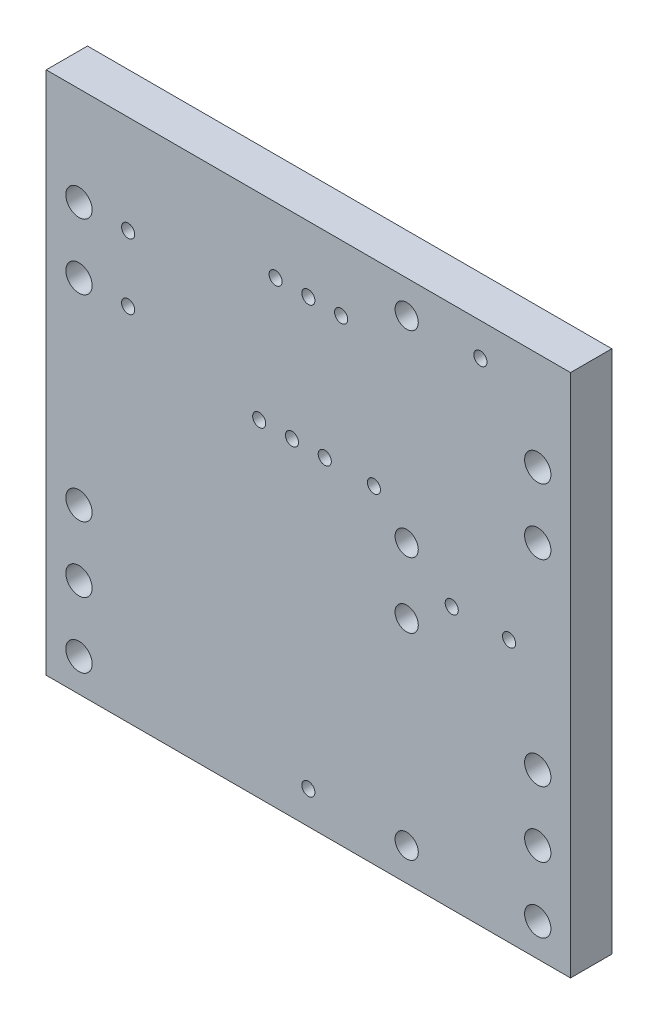
SolidWorks part; units mm, degrees
ref_plane "Front Plane" through (0, 0, 0) normal (0, 0, 1) x (1, 0, 0)
ref_plane "Top Plane" through (0, 0, 0) normal (0, 1, 0) x (1, 0, 0)
ref_plane "Right Plane" through (0, 0, 0) normal (1, 0, 0) x (0, 0, -1)
ref_plane "Dielectric_Layer Layer 1" through (0, 0, 1.6) normal (0, 0, 1) x (1, 0, 0)
sketch "Sketch1" plane through (0, 0, 0) normal (0, 0, 1) x (1, 0, 0)
  line L0 (0, 0) -> (20.32, 0)
  line L1 (20.32, 0) -> (20.32, 20.32)
  line L2 (20.32, 20.32) -> (0, 20.32)
  line L3 (0, 20.32) -> (0, 0)
extrude "Board_Outline" add sketch "Sketch1" along normal blind 1.6 separate body
sketch "Sketch2" plane through (0, 0, 0) normal (0, 0, 1) x (1, 0, 0)
  circle A0 centre (9.525, 12.7) radius 0.254
  circle A1 centre (11.43, 17.78) radius 0.254
  circle A2 centre (10.16, 17.78) radius 0.254
  circle A3 centre (10.795, 12.7) radius 0.254
  circle A4 centre (3.175, 13.97) radius 0.254
  circle A5 centre (8.89, 17.78) radius 0.254
  circle A6 centre (15.7163, 10.16) radius 0.254
  circle A7 centre (16.8275, 19.05) radius 0.254
  circle A8 centre (8.255, 12.7) radius 0.254
  circle A9 centre (17.9388, 10.16) radius 0.254
  circle A10 centre (12.7, 12.7) radius 0.254
  circle A11 centre (10.16, 1.27) radius 0.254
  circle A12 centre (3.175, 16.51) radius 0.254
extrude "NPTH" cut sketch "Sketch2" along normal through all
sketch "Sketch3" plane through (0, 0, 0) normal (0, 0, 1) x (1, 0, 0)
  circle A0 centre (1.27, 1.27) radius 0.51
  circle A1 centre (1.27, 3.81) radius 0.51
  circle A2 centre (1.27, 6.35) radius 0.51
  circle A3 centre (19.05, 16.51) radius 0.51
  circle A4 centre (19.05, 13.97) radius 0.51
  circle A5 centre (1.27, 16.51) radius 0.51
  circle A6 centre (1.27, 13.97) radius 0.51
  circle A7 centre (19.05, 1.27) radius 0.51
  circle A8 centre (19.05, 3.81) radius 0.51
  circle A9 centre (19.05, 6.35) radius 0.51
  circle A10 centre (13.97, 8.89) radius 0.45
  circle A11 centre (13.97, 1.27) radius 0.45
  circle A12 centre (13.97, 11.43) radius 0.45
  circle A13 centre (13.97, 19.05) radius 0.45
extrude "PTH" cut sketch "Sketch3" along normal through all
